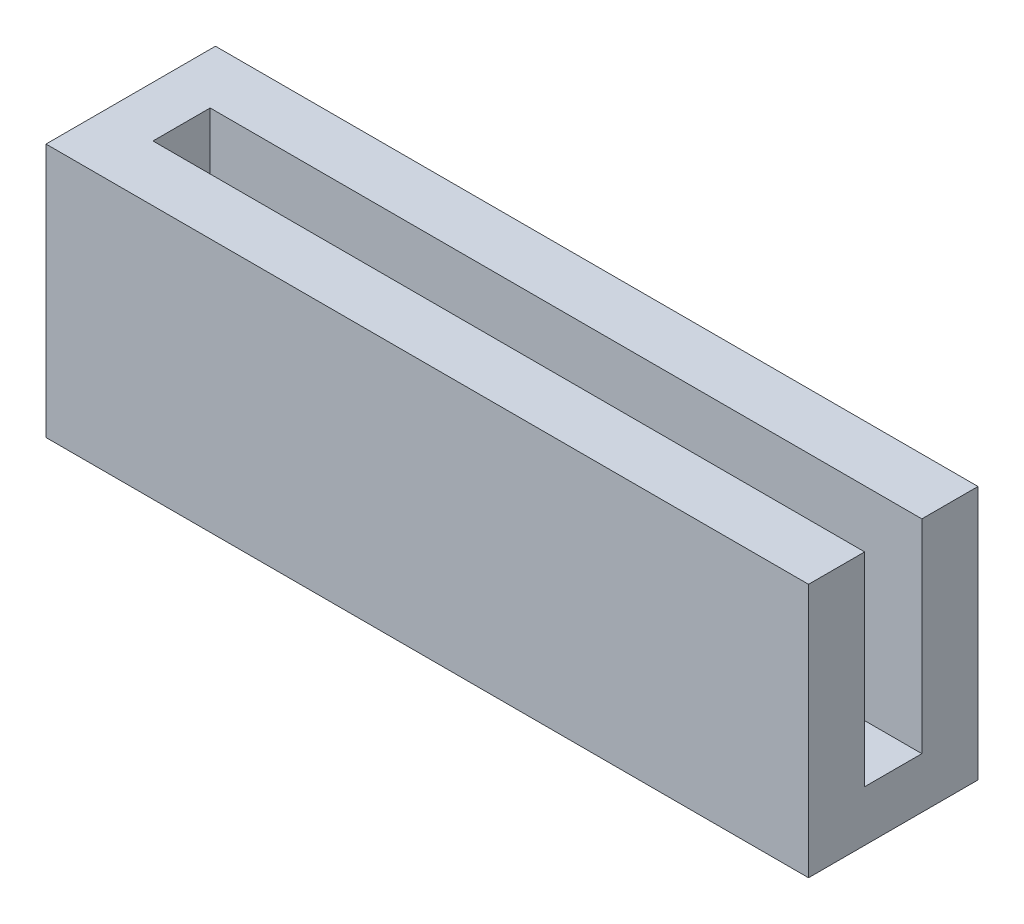
SolidWorks part; units mm, degrees
material "PET"
ref_plane "Front Plane" through (0, 0, 0) normal (0, 0, 1) x (1, 0, 0)
ref_plane "Top Plane" through (0, 0, 0) normal (0, 1, 0) x (1, 0, 0)
ref_plane "Right Plane" through (0, 0, 0) normal (1, 0, 0) x (0, 0, -1)
sketch "Sketch2" plane through (0, 0, 0) normal (0, 0, 1) x (1, 0, 0)
  line L1 (0, 0) -> (45, 0)
  line L2 (0, 0) -> (0, 15)
  line L3 (0, 15) -> (45, 15)
  line L4 (45, 0) -> (45, 15)
  dimension "D1" = 15
  dimension "D2" = 45
extrude "Boss-Extrude1" add sketch "Sketch2" along normal mid plane 10
sketch "Sketch3" plane through (0, 15, 0) normal (0, 1, 0) x (1, 0, 0)
  line L0 (45, -5) -> (45, 5) construction
  line L1 (3, -1.6875) -> (45, -1.6875)
  line L2 (3, -1.6875) -> (3, 1.6875)
  line L3 (3, 1.6875) -> (45, 1.6875)
  line L4 (45, -1.6875) -> (45, 1.6875)
  line L5 (3, -1.6875) -> (45, 1.6875) construction
  line L6 (3, 1.6875) -> (45, -1.6875) construction
  line L7 (0, -5) -> (0, 5) construction
  point P0 (24, 0)
  dimension "D1" = 3.375
  dimension "D2" = 3
extrude "Cut-Extrude1" cut sketch "Sketch3" against normal offset from surface (12 mm away) 3 up to face at (22.5, 0, 0)
